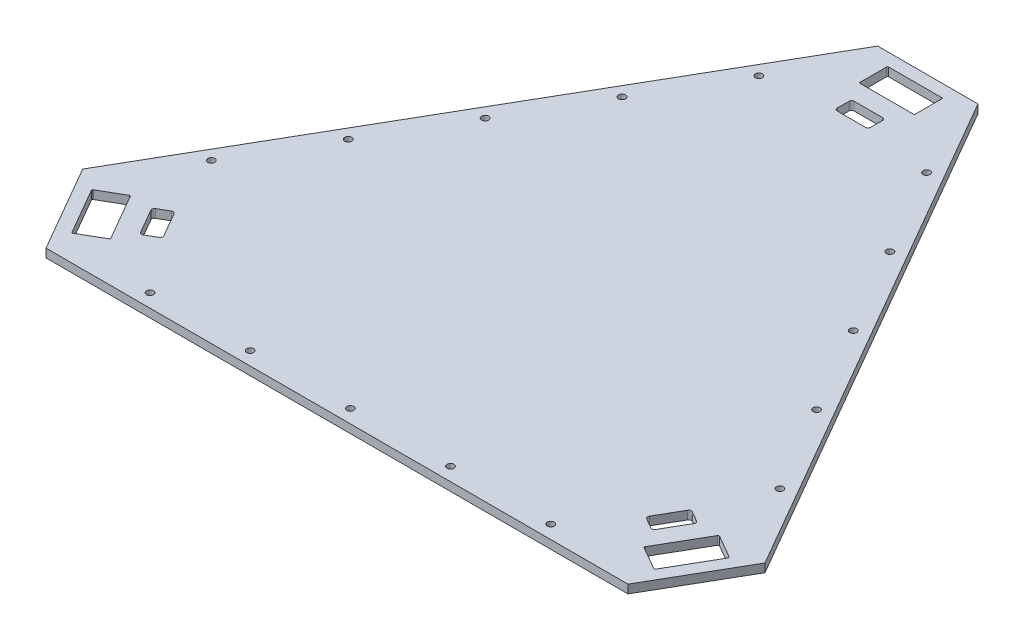
SolidWorks part; units mm, degrees
material "6061-T6 (SS)"
ref_plane "Front Plane" through (0, 0, 0) normal (0, 0, 1) x (1, 0, 0)
ref_plane "Top Plane" through (0, 0, 0) normal (0, 1, 0) x (1, 0, 0)
ref_plane "Right Plane" through (0, 0, 0) normal (1, 0, 0) x (0, 0, -1)
sketch "Sketch1" plane through (-388.2817, 0, -288.1857) normal (0, 1, 0) x (1, 0, 0)
  line L0 (1747.5708, -13084.8246) -> (1672.5144, -13084.8246)
  line L1 (1672.5144, -13084.8246) -> (1454.7035, -13462.0841)
  line L2 (1454.7035, -13462.0841) -> (1492.2317, -13527.0849)
  line L3 (1492.2317, -13527.0849) -> (1927.8535, -13527.0849)
  line L4 (1927.8535, -13527.0849) -> (1965.3817, -13462.0841)
  line L5 (1965.3817, -13462.0841) -> (1747.5708, -13084.8246)
  line L9 (1681.81, -13068.724) -> (1641.3158, -13138.8621) construction
  line L11 (1548.8311, -13527.0849) -> (1464.0303, -13527.0849) construction
  line L14 (1978.4206, -13484.668) -> (1947.1007, -13430.4205) construction
  line L64 (1710.0426, -13357.9978) -> (1856.4763, -13273.4543) construction
  line L65 (1710.0426, -13357.9978) -> (1710.0426, -13527.0849) construction
  line L66 (1710.0426, -13357.9978) -> (1563.6089, -13273.4543) construction
  line L68 (1730.6926, -13114.8746) -> (1730.6926, -13095.0746)
  line L69 (1729.9426, -13094.3246) -> (1690.1426, -13094.3246)
  line L70 (1690.1426, -13115.6246) -> (1729.9426, -13115.6246)
  line L71 (1689.3926, -13095.0746) -> (1689.3926, -13114.8746)
  line L98 (1492.6694, -13507.3429) -> (1509.8167, -13497.4429)
  line L99 (1510.0912, -13496.4184) -> (1490.1912, -13461.9506)
  line L100 (1471.7449, -13472.6006) -> (1491.6448, -13507.0684)
  line L101 (1489.1667, -13461.6761) -> (1472.0194, -13471.5761)
  line L126 (1948.0658, -13471.5761) -> (1930.9185, -13461.6761)
  line L127 (1910.2685, -13497.4429) -> (1927.4158, -13507.3429)
  line L128 (1928.4403, -13507.0684) -> (1948.3403, -13472.6006)
  line L129 (1929.894, -13461.9506) -> (1909.994, -13496.4184)
  circle A19 centre (1710.0426, -13357.9978) radius 150.5
  arc A23 (1729.9426, -13115.6246) -> (1730.6926, -13114.8746) centre (1729.9426, -13114.8746) ccw
  arc A24 (1730.6926, -13095.0746) -> (1729.9426, -13094.3246) centre (1729.9426, -13095.0746) ccw
  arc A25 (1690.1426, -13094.3246) -> (1689.3926, -13095.0746) centre (1690.1426, -13095.0746) ccw
  arc A26 (1689.3926, -13114.8746) -> (1690.1426, -13115.6246) centre (1690.1426, -13114.8746) ccw
  arc A45 (1509.8167, -13497.4429) -> (1510.0912, -13496.4184) centre (1509.4417, -13496.7934) ccw
  arc A46 (1491.6448, -13507.0684) -> (1492.6694, -13507.3429) centre (1492.2944, -13506.6934) ccw
  arc A47 (1490.1912, -13461.9506) -> (1489.1667, -13461.6761) centre (1489.5417, -13462.3256) ccw
  arc A48 (1472.0194, -13471.5761) -> (1471.7449, -13472.6006) centre (1472.3944, -13472.2256) ccw
  arc A53 (1927.4158, -13507.3429) -> (1928.4403, -13507.0684) centre (1927.7908, -13506.6934) ccw
  arc A59 (1948.3403, -13472.6006) -> (1948.0658, -13471.5761) centre (1947.6908, -13472.2256) ccw
  arc A60 (1930.9185, -13461.6761) -> (1929.894, -13461.9506) centre (1930.5435, -13462.3256) ccw
  arc A61 (1909.994, -13496.4184) -> (1910.2685, -13497.4429) centre (1910.6435, -13496.7934) ccw
  dimension "D1" = 301
extrude "Boss-Extrude1" add sketch "Sketch1" along normal blind 6.35 contours A19 | L4 L5 L0 L1 L2 L3 A61 L129 A60 L126 A59 L128 A53 L127 A48 L101 A47 L99 A45 L98 A46 L100 A26 L71 A25 L69 A24 L68 A23 L70 A19
sketch "Sketch3" plane through (0, 6.35, 0) normal (0, 1, 0) x (1, 0, 0)
  line L1 (1175.3272, -12985.2687) -> (1188.9457, -12993.1313) construction
  circle A0 centre (1183.9875, -12990.2687) radius 2.6
  circle A1 centre (1146.4875, -13055.2206) radius 2.6
  circle A2 centre (1108.9875, -13120.1725) radius 2.6
  circle A3 centre (1221.4875, -12925.3168) radius 2.6
  circle A4 centre (1258.9875, -12860.3649) radius 2.6
  circle A5 centre (1459.5343, -12990.2687) radius 2.6
  circle A6 centre (1497.0343, -13055.2206) radius 2.6
  circle A7 centre (1534.5343, -13120.1725) radius 2.6
  circle A8 centre (1422.0343, -12925.3168) radius 2.6
  circle A9 centre (1384.5343, -12860.3649) radius 2.6
  circle A10 centre (1321.7609, -13228.8992) radius 2.6
  circle A11 centre (1246.7609, -13228.8992) radius 2.6
  circle A12 centre (1171.7609, -13228.8992) radius 2.6
  circle A13 centre (1396.7609, -13228.8992) radius 2.6
  circle A14 centre (1471.7609, -13228.8992) radius 2.6
  point P37 (1321.7609, -13069.8122)
  dimension "D3" = 3
  dimension "D4" = 3
  dimension "D5" = 3
extrude "Cut-Extrude2" cut sketch "Sketch3" against normal blind 10
sketch "Sketch4" plane through (0, 6.35, 0) normal (0, 1, 0) x (1, 0, 0)
  line L0 (1118.5606, -13175.0055) -> (1129.0606, -13193.1921)
  line L2 (1119.2927, -13172.2735) -> (1126.8271, -13167.9235)
  line L3 (1131.7927, -13193.9241) -> (1139.3271, -13189.5741)
  line L4 (1129.5591, -13168.6555) -> (1140.0591, -13186.8421)
  line L5 (1468.1946, -12985.2687) -> (1321.7609, -13069.8122) construction
  line L6 (1577.1, -13173.8984) -> (1359.2891, -12796.6389) construction
  line L7 (1321.7609, -13238.8992) -> (1321.7609, -13069.8122) construction
  line L8 (1103.95, -13238.8992) -> (1539.5717, -13238.8992) construction
  line L9 (1175.3272, -12985.2687) -> (1321.7609, -13069.8122) construction
  line L10 (1284.2326, -12796.6389) -> (1066.4218, -13173.8984) construction
  line L11 (1332.2609, -12841.2389) -> (1311.2609, -12841.2389)
  line L12 (1334.2609, -12843.2389) -> (1334.2609, -12851.9389)
  line L13 (1309.2609, -12843.2389) -> (1309.2609, -12851.9389)
  line L14 (1332.2609, -12853.9389) -> (1311.2609, -12853.9389)
  line L15 (1514.4611, -13193.1921) -> (1524.9611, -13175.0055)
  line L16 (1511.7291, -13193.9241) -> (1504.1947, -13189.5741)
  line L17 (1524.2291, -13172.2735) -> (1516.6947, -13167.9235)
  line L18 (1503.4626, -13186.8421) -> (1513.9626, -13168.6555)
  line L19 (1121.8095, -13208.2327) -> (1101.9095, -13173.7649) construction
  line L20 (1123.8106, -13184.0988) -> (1111.8595, -13190.9988) construction
  arc A0 (1126.8271, -13167.9235) -> (1129.5591, -13168.6555) centre (1127.8271, -13169.6555) cw
  arc A1 (1139.3271, -13189.5741) -> (1140.0591, -13186.8421) centre (1138.3271, -13187.8421) ccw
  arc A2 (1334.2609, -12851.9389) -> (1332.2609, -12853.9389) centre (1332.2609, -12851.9389) cw
  arc A3 (1309.2609, -12851.9389) -> (1311.2609, -12853.9389) centre (1311.2609, -12851.9389) ccw
  arc A4 (1504.1947, -13189.5741) -> (1503.4626, -13186.8421) centre (1505.1947, -13187.8421) cw
  arc A5 (1516.6947, -13167.9235) -> (1513.9626, -13168.6555) centre (1515.6947, -13169.6555) ccw
  arc A6 (1131.7927, -13193.9241) -> (1129.0606, -13193.1921) centre (1130.7927, -13192.1921) cw
  arc A7 (1118.5606, -13175.0055) -> (1119.2927, -13172.2735) centre (1120.2927, -13174.0055) cw
  arc A8 (1311.2609, -12841.2389) -> (1309.2609, -12843.2389) centre (1311.2609, -12843.2389) ccw
  arc A9 (1334.2609, -12843.2389) -> (1332.2609, -12841.2389) centre (1332.2609, -12843.2389) ccw
  arc A10 (1514.4611, -13193.1921) -> (1511.7291, -13193.9241) centre (1512.7291, -13192.1921) cw
  arc A11 (1524.9611, -13175.0055) -> (1524.2291, -13172.2735) centre (1523.2291, -13174.0055) ccw
  point P5 (1121.9846, -13208.5361)
  point P25 (1130.0606, -13194.9241)
  point P27 (1301.5106, -12827.4389)
  point P36 (1541.7874, -13173.4616)
  point P42 (1321.7609, -13069.8122)
  point P45 (1117.5606, -13173.2735)
  dimension "D2" = 2
  dimension "D6" = 2
  dimension "D4" = 2
  dimension "D8" = 2
  dimension "D1" = 25
  dimension "D3" = 12.7
  dimension "D7" = 26.5
  dimension "D5" = 3
extrude "Cut-Extrude3" cut sketch "Sketch4" against normal blind 10
